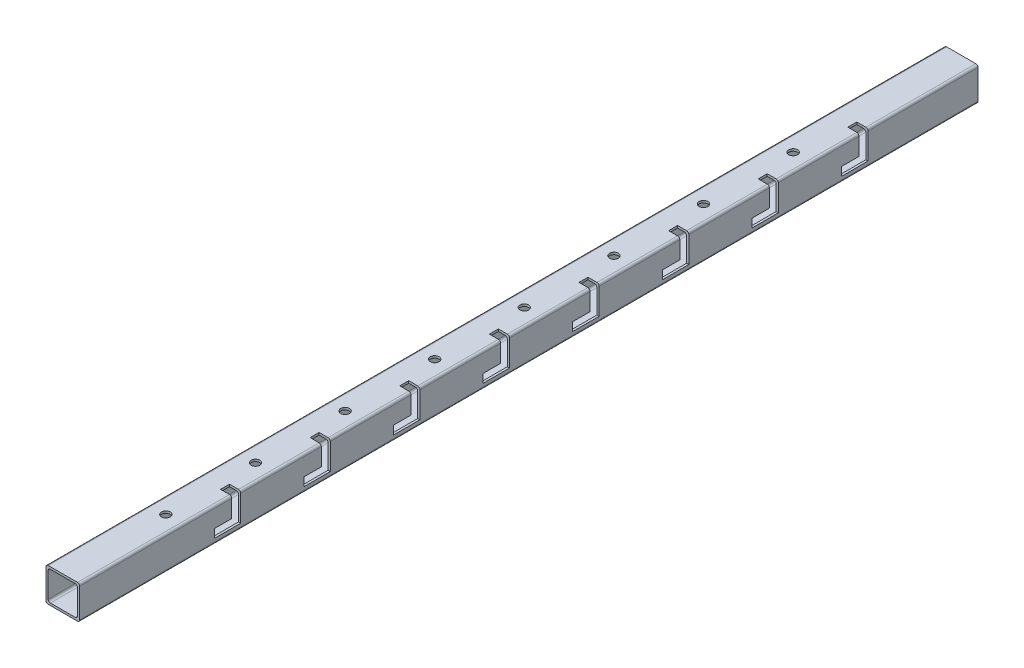
SolidWorks part; units mm, degrees
ref_plane "Front Plane" through (0, 0, 0) normal (0, 0, 1) x (1, 0, 0)
ref_plane "Top Plane" through (0, 0, 0) normal (0, 1, 0) x (1, 0, 0)
ref_plane "Right Plane" through (0, 0, 0) normal (1, 0, 0) x (0, 0, -1)
sketch "Sketch1" plane through (0, 0, 0) normal (0, 0, 1) x (1, 0, 0)
  line L0 (-9.525, 0) -> (9.525, 0) construction
  line L1 (0, -9.525) -> (0, 9.525) construction
  line L2 (8.2804, 0) -> (8.2804, 8.2804) construction
  line L3 (-9.525, -9.525) -> (9.525, -9.525) construction
  line L4 (-9.525, -9.525) -> (-9.525, 9.525) construction
  line L5 (-9.525, 9.525) -> (9.525, 9.525) construction
  line L6 (9.525, -9.525) -> (9.525, 9.525) construction
  line L7 (-9.525, -9.525) -> (9.525, 9.525) construction
  line L8 (-9.525, 9.525) -> (9.525, -9.525) construction
  line L9 (8.2804, 8.2804) -> (-8.2804, 8.2804) construction
  line L10 (-8.2804, 8.2804) -> (-8.2804, -8.2804) construction
  line L11 (-8.2804, -8.2804) -> (8.2804, -8.2804) construction
  line L12 (8.2804, -8.2804) -> (8.2804, 0) construction
  point P0 (0, 0)
  point P4 (0, 0)
  point P9 (0, 0)
  point P10 (8.2804, 0)
  point P13 (0, -8.2804)
  point P14 (-8.2804, 0)
  point P15 (0, 8.2804)
  dimension "Width" = 19.05
  dimension "Wall Thickness" = 1.2446
  dimension "Height" = 19.05
  dimension "D1" = 1.2446
  dimension "D2" = 1.2446
  dimension "D3" = 1.2446
sketch "Sketch2" plane through (0, 0, 0) normal (1, 0, 0) x (0, 0, -1)
  line L0 (254.635, 9.525) -> (-254.635, 9.525) construction
  point P3 (-232.7275, 9.525)
  point P5 (232.7275, 9.525)
  point P7 (0, 9.525)
  dimension "D1" = 21.9075
  dimension "D2" = 21.9075
  dimension "Length" = 509.27
sketch "Sketch3" plane through (0, 0, 0) normal (0, 0, 1) x (1, 0, 0)
  line L1 (9.525, 9.525) -> (-9.525, 9.525)
  line L2 (-9.525, 9.525) -> (-9.525, -9.525)
  line L3 (-9.525, -9.525) -> (9.525, -9.525) construction
  line L4 (-9.525, -9.525) -> (9.525, -9.525)
  line L5 (9.525, -9.525) -> (9.525, 9.525)
  line L6 (-8.2804, 8.2804) -> (8.2804, 8.2804)
  line L7 (8.2804, 8.2804) -> (8.2804, -8.2804)
  line L8 (8.2804, -8.2804) -> (-8.2804, -8.2804)
  line L9 (-8.2804, -8.2804) -> (-8.2804, 8.2804)
extrude "Boss-Extrude1" add sketch "Sketch3" along normal mid plane 509.27
fillet "Fillet1" radius 1.2446 8 edges at (-9.525, 9.525, 0) (8.2804, -8.2804, 0) (-8.2804, -8.2804, 0) (-8.2804, 8.2804, 0) (8.2804, 8.2804, 0) (9.525, -9.525, 0) (-9.525, -9.525, 0) (9.525, 9.525, 0)
sketch "Sketch4" plane through (0, 9.525, 0) normal (0, 1, 0) x (1, 0, 0)
  line L0 (0, 254.635) -> (0, 159.385) construction
  line L1 (8.2804, 254.635) -> (-8.2804, 254.635) construction
  line L2 (0, 159.385) -> (0, 108.585) construction
  circle A0 centre (0, 159.385) radius 2.4892
  circle A1 centre (0, 108.585) radius 2.4892
  circle A2 centre (0, 57.785) radius 2.4892
  circle A3 centre (0, 6.985) radius 2.4892
  circle A4 centre (0, -43.815) radius 2.4892
  circle A5 centre (0, -94.615) radius 2.4892
  circle A6 centre (0, -145.415) radius 2.4892
  circle A7 centre (0, -196.215) radius 2.4892
  dimension "D2" = 4.9784
  dimension "D4" = 4.9784
  dimension "D1" = 95.25
  dimension "D3" = 50.8
  dimension "D5" = 7
extrude "Cut-Extrude1" cut sketch "Sketch4" against normal through all
sketch "Sketch6" plane through (-9.525, 0, 0) normal (-1, 0, 0) x (0, 0, 1)
  line L0 (-254.635, 0) -> (-179.705, 0) construction
  line L1 (-254.635, 8.2804) -> (-254.635, -8.2804) construction
  line L2 (-182.118, -1.651) -> (-187.198, -1.651)
  line L7 (-182.118, -6.477) -> (-177.292, -1.651) construction
  line L12 (-177.292, -6.477) -> (-182.118, -6.477)
  line L13 (-177.292, -6.477) -> (-177.292, -1.651)
  line L14 (-177.292, -1.651) -> (-182.118, -1.651)
  line L15 (-182.118, -6.477) -> (-182.118, -1.651) construction
  line L16 (-192.278, 9.525) -> (-192.278, -6.477)
  line L17 (-177.292, -6.477) -> (-182.118, -1.651) construction
  line L18 (-254.635, 9.525) -> (254.635, 9.525) construction
  line L19 (-192.278, -6.477) -> (-182.118, -6.477)
  line L20 (-187.198, -1.651) -> (-187.198, 9.525)
  line L21 (-187.198, 9.525) -> (-192.278, 9.525)
  point P12 (-179.705, -4.064)
  dimension "D1" = 74.93
  dimension "D2" = 16.002
  dimension "D3" = 4.826
  dimension "D4" = 4.826
  dimension "D5" = 10.16
  dimension "D6" = 5.08
extrude "Cut-Extrude3" cut sketch "Sketch6" along normal blind 6.35 from surface at -19.05 starting at face at (9.525, 0, 0)
pattern_linear "LPattern2" count 8 spacing 50.8 along (0, 0, 1) of "Cut-Extrude3"
equation "\"D1@Boss-Extrude1\" = \"Length@Sketch2\""
equation "\"D1@Sketch2\" = \"Width@Sketch1\" * 1.15"
equation "\"D2@Sketch2\"=\"D1@Sketch2\""
equation "\"D1@Sketch1\"=\"Wall Thickness@Sketch1\""
equation "\"D2@Sketch1\"=\"Wall Thickness@Sketch1\""
equation "\"D3@Sketch1\"=\"Wall Thickness@Sketch1\""
equation "\"D1@Fillet1\"=\"Wall Thickness@Sketch1\""
